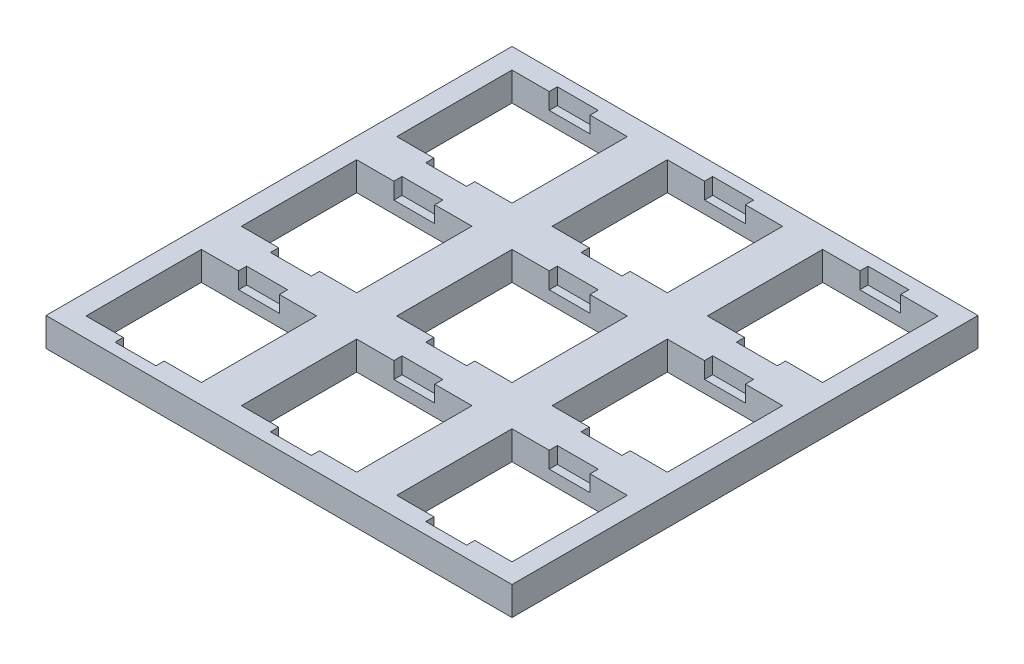
SolidWorks part; units mm, degrees
ref_plane "Plan de face" through (0, 0, 0) normal (0, 0, 1) x (1, 0, 0)
ref_plane "Plan de dessus" through (0, 0, 0) normal (0, 1, 0) x (1, 0, 0)
ref_plane "Plan de droite" through (0, 0, 0) normal (1, 0, 0) x (0, 0, -1)
sketch "Esquisse2" plane through (0, 0, 0) normal (0, 1, 0) x (1, 0, 0)
  line L1 (28.5, -28.5) -> (-28.5, -28.5)
  line L2 (28.5, -28.5) -> (28.5, 28.5)
  line L3 (28.5, 28.5) -> (-28.5, 28.5)
  line L4 (-28.5, -28.5) -> (-28.5, 28.5)
  line L5 (28.5, -28.5) -> (-28.5, 28.5) construction
  line L6 (28.5, 28.5) -> (-28.5, -28.5) construction
  point P0 (0, 0)
  dimension "D1" = 57
  dimension "D2" = 57
extrude "Boss.-Extru.1" add sketch "Esquisse2" along normal blind 3.5 contours L3 L4 L1 L2
sketch "Esquisse3" plane through (0, 3.5, 0) normal (0, 1, 0) x (1, 0, 0)
  line L1 (-26, 26) -> (-11.9, 26)
  line L2 (-26, 26) -> (-26, 11.9)
  line L3 (-26, 11.9) -> (-11.9, 11.9)
  line L4 (-11.9, 26) -> (-11.9, 11.9)
  dimension "D1" = 14.1
  dimension "D2" = 14.1
extrude "Enlèv. mat.-Extru.1" cut sketch "Esquisse3" against normal blind 3.5
sketch "Esquisse4" plane through (0, 3.5, 0) normal (0, 1, 0) x (1, 0, 0)
  line L0 (-11.9, 26) -> (-26, 26) construction
  line L1 (-21.45, 27) -> (-16.45, 27)
  line L2 (-21.45, 27) -> (-21.45, 25)
  line L3 (-21.45, 25) -> (-16.45, 25)
  line L4 (-16.45, 27) -> (-16.45, 25)
  line L5 (-21.45, 27) -> (-16.45, 25) construction
  line L6 (-21.45, 25) -> (-16.45, 27) construction
  line L7 (-26, 11.9) -> (-11.9, 11.9) construction
  line L8 (-21.45, 12.9) -> (-16.45, 12.9)
  line L9 (-21.45, 12.9) -> (-21.45, 10.9)
  line L10 (-21.45, 10.9) -> (-16.45, 10.9)
  line L11 (-16.45, 12.9) -> (-16.45, 10.9)
  line L12 (-21.45, 12.9) -> (-16.45, 10.9) construction
  line L13 (-21.45, 10.9) -> (-16.45, 12.9) construction
  point P0 (-18.95, 26)
  point P7 (-18.95, 11.9)
  dimension "D1" = 5
  dimension "D2" = 5
  dimension "D3" = 2
  dimension "D4" = 2
extrude "Enlèv. mat.-Extru.2" cut sketch "Esquisse4" against normal blind 2
pattern_linear "Répétition linéaire1" count 3 spacing 19 along (1, 0, 0) count 3 spacing 19 along (0, 0, 1) of "Enlèv. mat.-Extru.2", "Enlèv. mat.-Extru.1"
